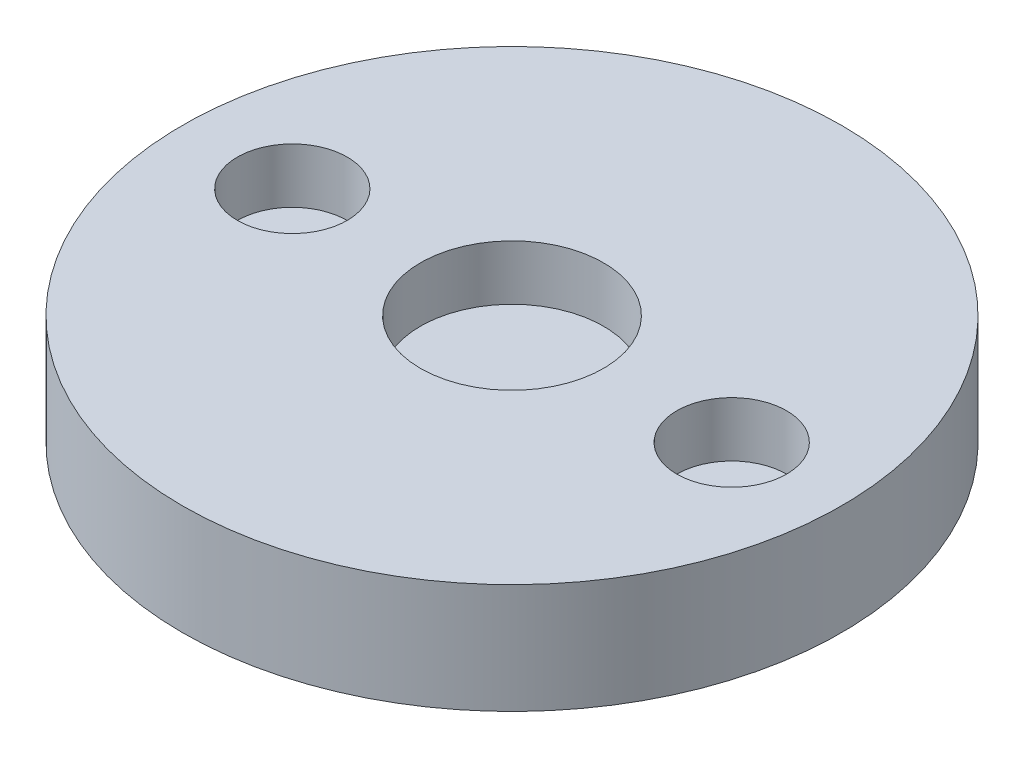
SolidWorks part; units mm, degrees
ref_plane "Front Plane" through (0, 0, 0) normal (0, 0, 1) x (1, 0, 0)
ref_plane "Top Plane" through (0, 0, 0) normal (0, 1, 0) x (1, 0, 0)
ref_plane "Right Plane" through (0, 0, 0) normal (1, 0, 0) x (0, 0, -1)
sketch "Sketch1" plane through (0, 0, 0) normal (0, 1, 0) x (1, 0, 0)
  circle A0 centre (0, 0) radius 9
  dimension "D1" = 18
extrude "Boss-Extrude1" add sketch "Sketch1" along normal blind 3
sketch "Sketch2" plane through (0, 3, 0) normal (0, 1, 0) x (1, 0, 0)
  circle A0 centre (0, 0) radius 2.5
  circle A1 centre (-6, 0) radius 1.5
  circle A2 centre (6, 0) radius 1.5
  circle A3 centre (0, 0) radius 9 construction
  dimension "D1" = 5
  dimension "D2" = 6
  dimension "D3" = 3
  dimension "D4" = 3
  dimension "D5" = 6
extrude "Cut-Extrude1" cut sketch "Sketch2" against normal blind 1.5
